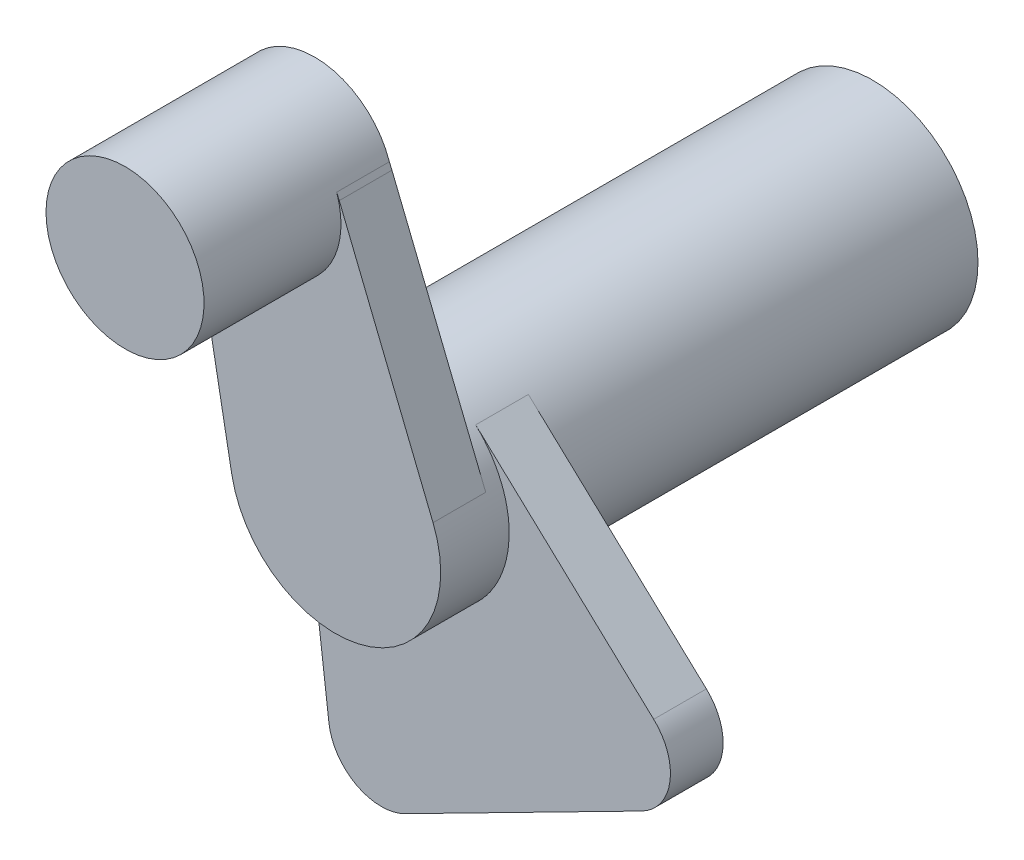
SolidWorks part; units mm, degrees
ref_plane "Front Plane" through (0, 0, 0) normal (0, 0, 1) x (1, 0, 0)
ref_plane "Top Plane" through (0, 0, 0) normal (0, 1, 0) x (1, 0, 0)
ref_plane "Right Plane" through (0, 0, 0) normal (1, 0, 0) x (0, 0, -1)
sketch "Sketch1" plane through (0, 0, 0) normal (0, 0, 1) x (1, 0, 0)
  circle A0 centre (0, 0) radius 20
  dimension "D1" = 40
extrude "Boss-Extrude1" add sketch "Sketch1" along normal blind 102
ref_plane "Plane1" through (0, 0, 89) normal (0, 0, 1) x (1, 0, 0)
sketch "Sketch2" plane through (0, 0, 89) normal (0, 0, 1) x (1, 0, 0)
  line L0 (-14.2153, -48.3011) -> (-19.8507, -2.4392)
  line L1 (0.2508, -55.9911) -> (45.1565, -33.1053)
  line L2 (47.4351, -16.8815) -> (13.6386, 14.6283)
  circle A0 centre (0, 0) radius 20
  arc A1 (45.1565, -33.1053) -> (47.4351, -16.8815) centre (40.6157, -24.1957) ccw
  arc A2 (0.2508, -55.9911) -> (-14.2153, -48.3011) centre (-4.2899, -47.0815) cw
  dimension "D2" = 40
  dimension "D5" = 10
  dimension "D1" = 50
  dimension "D3" = 70
  dimension "D4" = 70
extrude "Boss-Extrude2" add sketch "Sketch2" against normal blind 10 contours A2 L1 A1 L2 A0 L0
sketch "Sketch3" plane through (0, 0, 102) normal (0, 0, 1) x (1, 0, 0)
  line L0 (19.3085, 5.5996) -> (0.7393, 51.5478)
  line L1 (47.4351, -16.8815) -> (13.6386, 14.6283) construction
  line L2 (-28.6831, 45.0925) -> (-19.6662, -3.6389)
  line L3 (0.7393, 51.5478) -> (0.253, 52.6944)
  arc A0 (-19.6662, -3.6389) -> (18.543, 7.4938) centre (0, 0) ccw
  arc A1 (0.253, 52.6944) -> (-28.6831, 45.0925) centre (-13.9335, 47.8217) ccw
  circle M3 centre (0, 0) radius 20
  dimension "D2" = 40
  dimension "D3" = 30
  dimension "D1" = 155
extrude "Boss-Extrude3" add sketch "Sketch3" against normal blind 10 contours L3 A1 L2 L0 M3 | M3
sketch "Sketch4" plane through (0, 0, 92) normal (0, 0, -1) x (-1, 0, 0)
  circle A0 centre (13.9335, 47.8217) radius 15
  dimension "D1" = 30
extrude "Boss-Extrude4" add sketch "Sketch4" against normal blind 36
